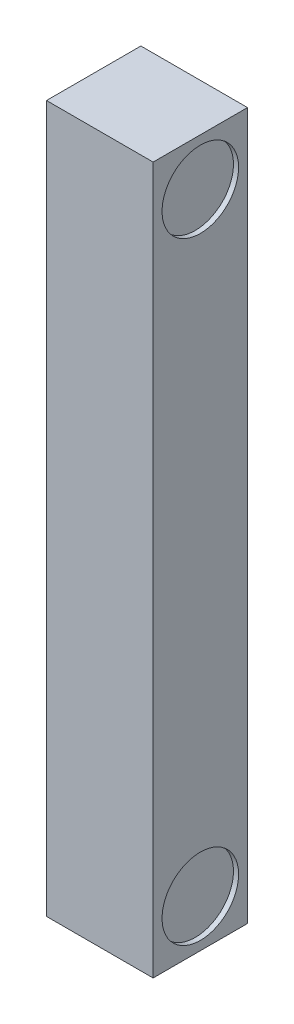
SolidWorks part; units mm, degrees
material "Maple"
ref_plane "Front Plane" through (0, 0, 0) normal (0, 0, 1) x (1, 0, 0)
ref_plane "Top Plane" through (0, 0, 0) normal (0, 1, 0) x (1, 0, 0)
ref_plane "Right Plane" through (0, 0, 0) normal (1, 0, 0) x (0, 0, -1)
sketch "Sketch1" plane through (0, 0, 0) normal (1, 0, 0) x (0, 0, -1)
  line L1 (-18.5, -138.5) -> (18.5, -138.5)
  line L2 (-18.5, -138.5) -> (-18.5, 138.5)
  line L3 (-18.5, 138.5) -> (18.5, 138.5)
  line L4 (18.5, -138.5) -> (18.5, 138.5)
  line L5 (-18.5, -138.5) -> (18.5, 138.5) construction
  line L6 (-18.5, 138.5) -> (18.5, -138.5) construction
  point P0 (0, 0)
  dimension "D1" = 37
  dimension "D2" = 277
extrude "Boss-Extrude1" add sketch "Sketch1" along normal blind 41.8
sketch "Sketch2" plane through (41.8, 0, 0) normal (1, 0, 0) x (0, 0, -1)
  line L0 (0, 120) -> (0, -120) construction
  circle A0 centre (0, 120) radius 15
  circle A1 centre (0, -120) radius 15
  dimension "D2" = 30
  dimension "D3" = 30
  dimension "D1" = 240
extrude "Cut-Extrude1" cut sketch "Sketch2" against normal blind 2
sketch3d "URDF Reference"
  line L0 (0, 0, 0) -> (10, 0, 0) construction
  line L1 (0, 0, 0) -> (0, 0, -10) construction
  point P0 (0, 0, 0)
  point P1 (0, 0, 0)
